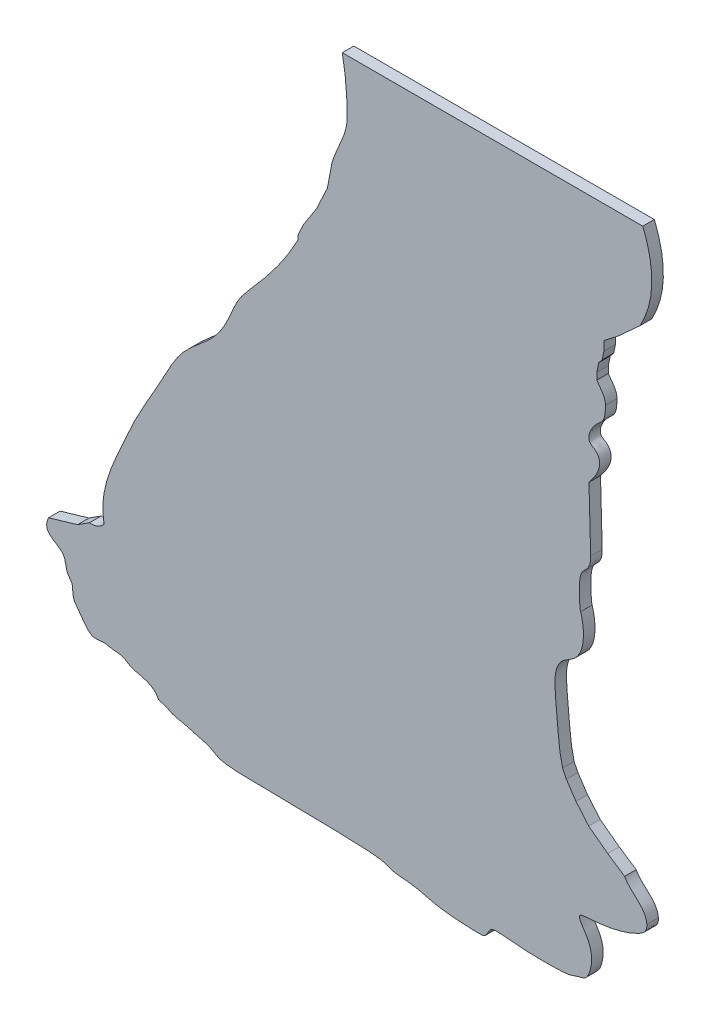
SolidWorks part; units mm, degrees
ref_plane "Front Plane" through (0, 0, 0) normal (0, 0, 1) x (1, 0, 0)
ref_plane "Top Plane" through (0, 0, 0) normal (0, 1, 0) x (1, 0, 0)
ref_plane "Right Plane" through (0, 0, 0) normal (1, 0, 0) x (0, 0, -1)
sketch "Sketch1" plane through (0, 0, 0) normal (0, 0, 1) x (1, 0, 0)
  line L0 (134.6667, 500.5) -> (673.3333, 500.5) construction
  line L2 (167.2022, 42.2012) -> (162.5517, 45.3095)
  line L3 (162.5517, 45.3095) -> (157.3147, 49.2233)
  line L4 (157.3147, 49.2233) -> (153.7929, 53.3936)
  line L5 (153.7929, 53.3936) -> (151.1787, 57.3127)
  line L6 (151.1787, 57.3127) -> (150.1126, 59.4633)
  line L7 (157.3755, 131.2295) -> (157.854, 113.8805)
  line L8 (159.5344, 156.6595) -> (159.5344, 158.498)
  line L9 (159.5344, 158.498) -> (160.0825, 161.1123)
  line L10 (160.0825, 161.1123) -> (161.0243, 162.2425)
  line L11 (161.0243, 162.2425) -> (161.5128, 164.5724)
  line L12 (161.5128, 164.5724) -> (161.5128, 167.1023)
  line L13 (161.5128, 167.1023) -> (165.1835, 169.9013)
  line L14 (165.1835, 169.9013) -> (171.472, 175.6217)
  line L15 (86.5908, 171.7678) -> (85.3882, 165.3811)
  line L16 (89.473, 199.6877) -> (172.1964, 199.6877)
  line L17 (85.3882, 165.3811) -> (82.4023, 158.9826)
  line L18 (82.4023, 158.9826) -> (78.8266, 153.4325)
  line L19 (78.8266, 153.4325) -> (77.3096, 150.1819)
  line L20 (77.3096, 150.1819) -> (77.3096, 148.973)
  spline S0 degree 1 poles (8.6124, 48.3831) (16.6111, 50.7357) knots 0 0 1 1
  spline S1 degree 1 poles (19.9047, 52.853) (16.6111, 50.7357) knots 0 0 1 1
  spline S2 degree 3 poles (23.9041, 54.4997) (22.542, 62.0444) (27.1512, 71.7199) (33.1716, 85.6736) (39.4703, 95.7444) (45.0444, 107.3971) (54.1548, 113.0729) (58.3579, 120.6747) (60.6418, 126.7915) (68.4166, 135.2748) (73.9208, 142.4894) (77.3096, 148.973) knots 0 0 0 0 0.194457 0.285904 0.412664 0.517827 0.629269 0.691339 0.750377 0.804905 1 1 1 1
  spline S3 degree 2 poles (19.9047, 52.853) (22.4371, 52.6083) (23.9041, 54.4997) knots 0 0 0 1 1 1
  spline S4 degree 3 poles (8.6124, 48.3831) (6.5691, 43.9628) (13.6478, 43.7296) (13.2535, 37.9915) (15.2259, 36.1128) (15.2445, 34.2074) (15.4257, 32.4092) (16.9812, 30.3171) (18.455, 28.2086) (20.7273, 25.6089) (23.6404, 26.5196) (26.3788, 25.705) (29.0077, 25.795) (31.226, 24.0079) (34.9468, 23.3493) (38.0007, 22.2222) (38.8831, 20.145) knots 0 0 0 0 0.18572 0.273851 0.320038 0.350192 0.393849 0.435551 0.514834 0.569195 0.638874 0.687587 0.755837 0.801068 0.865551 1 1 1 1
  spline S5 degree 3 poles (38.8831, 20.145) (41.2875, 19.5656) (42.3458, 18.5073) (45.4199, 18.1546) (49.7538, 16.7939) (52.7775, 16.1892) (54.7934, 14.8285) (56.3556, 14.1734) (60.1352, 13.7702) (61.5463, 13.7702) (99.2418, 13.2159) (101.2856, 12.2232) (103.9594, 11.2977) (106.3246, 11.2977) (111.5693, 10.5778) (115.1686, 9.2409) (123.9098, 8.5211) (128.0233, 8.5211) (128.9488, 8.7267) (129.9772, 10.7835) (131.0055, 11.8119) (139.3353, 10.7835) (144.7857, 10.7835) (151.9843, 10.7835) (154.3496, 12.1204) (156.7148, 12.1204) (158.1545, 16.0282) (158.1545, 19.319) (157.3318, 21.6842) (156.4063, 23.3296) (153.7325, 27.1346) (157.3189, 27.1346) (163.0629, 27.7755) (167.4392, 28.9243) (170.3933, 30.1004) (172.855, 31.5228) (173.32, 32.5895) (173.32, 33.793) knots 0 0 0 0 0.028571 0.057143 0.085714 0.114286 0.142857 0.171429 0.2 0.228571 0.257143 0.285714 0.314286 0.342857 0.371429 0.4 0.428571 0.457143 0.485714 0.514286 0.542857 0.571429 0.6 0.628571 0.657143 0.685714 0.714286 0.742857 0.771429 0.8 0.828571 0.857143 0.885714 0.914286 0.942857 0.971429 1 1 1 1
  spline S6 degree 3 poles (173.32, 33.793) (173.0564, 37.6266) (168.8406, 39.1122) (167.2022, 42.2012) knots 0 0 0 0 1 1 1 1
  spline S7 degree 3 poles (150.1126, 59.4633) (148.9568, 63.837) (148.9486, 71.4394) (146.8505, 84.0514) (156.4694, 88.1502) (156.2475, 95.5102) (155.0853, 99.2556) knots 0 0 0 0 0.308783 0.618237 0.704406 1 1 1 1
  spline S8 degree 3 poles (157.854, 113.8805) (157.8564, 113.8699) (157.8506, 110.688) (155.3081, 109.3846) (154.4188, 105.0533) (154.8696, 99.4834) (155.0853, 99.2556) knots 0 0 0 0 0.124799 0.365608 0.555267 1 1 1 1
  spline S9 degree 3 poles (161.8927, 151.8072) (161.9125, 149.0313) (161.4499, 147.7916) (158.4451, 145.386) (156.1309, 141.3803) (158.8302, 140.0435) (161.6487, 137.4079) (159.4597, 133.7277) (157.3755, 131.2295) knots 0 0 0 0 0.190659 0.228613 0.488803 0.534056 0.585176 1 1 1 1
  spline S10 degree 3 poles (159.5344, 156.6595) (160.7867, 154.8399) (162.0055, 153.6124) (161.8927, 151.8072) knots 0 0 0 0 1 1 1 1
  spline S11 degree 2 poles (172.1964, 199.6877) (177.5125, 186.6119) (171.472, 175.6217) knots 0 0 0 1 1 1
  spline S12 degree 3 poles (89.473, 199.6877) (90.4497, 194.8375) (90.826, 189.8378) (90.8383, 180.2807) (87.6783, 176.1914) (86.5908, 171.7678) knots 0 0 0 0 0.517811 0.520823 1 1 1 1
extrude "Boss-Extrude2" add sketch "Sketch1" along normal blind 3.175
